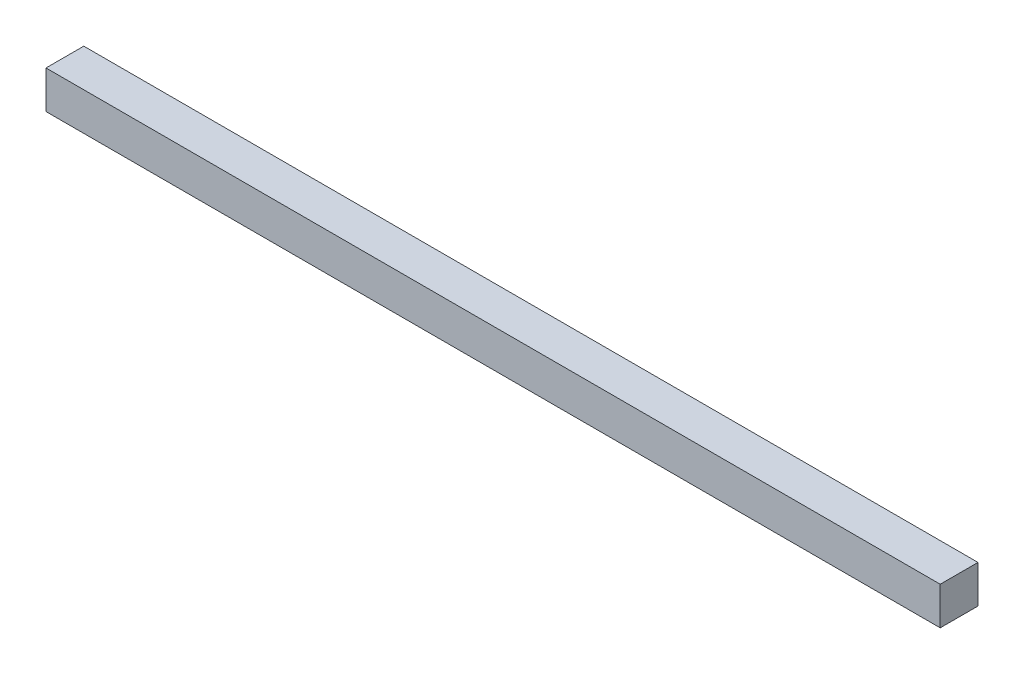
SolidWorks part; units mm, degrees
ref_plane "Front Plane" through (0, 0, 0) normal (0, 0, 1) x (1, 0, 0)
ref_plane "Top Plane" through (0, 0, 0) normal (0, 1, 0) x (1, 0, 0)
ref_plane "Right Plane" through (0, 0, 0) normal (1, 0, 0) x (0, 0, -1)
sketch "Sketch1" plane through (0, 0, 0) normal (0, 1, 0) x (1, 0, 0)
  line L1 (0, 0) -> (710, 0)
  line L2 (0, 0) -> (0, 30)
  line L3 (0, 30) -> (710, 30)
  line L4 (710, 0) -> (710, 30)
  dimension "D1" = 30
  dimension "D2" = 710
extrude "Boss-Extrude1" add sketch "Sketch1" along normal blind 30
